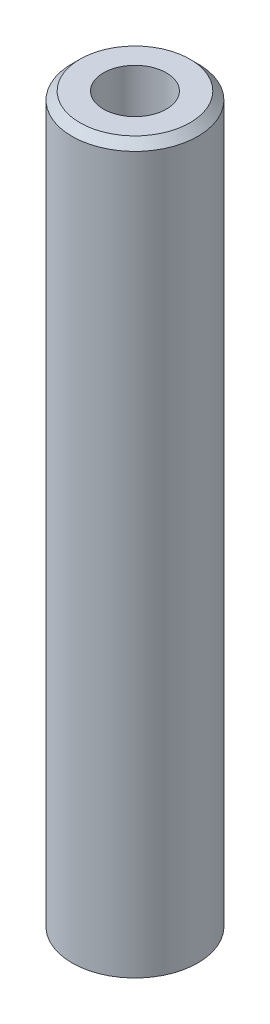
SolidWorks part; units mm, degrees
ref_plane "Front Plane" through (0, 0, 0) normal (0, 0, 1) x (1, 0, 0)
ref_plane "Top Plane" through (0, 0, 0) normal (0, 1, 0) x (1, 0, 0)
ref_plane "Right Plane" through (0, 0, 0) normal (1, 0, 0) x (0, 0, -1)
sketch "Sketch1" plane through (0, 0, 0) normal (0, 1, 0) x (1, 0, 0)
  circle A0 centre (0, 0) radius 2
  circle A1 centre (0, 0) radius 4
  dimension "D1" = 4
  dimension "D2" = 2
extrude "Boss-Extrude1" add sketch "Sketch1" along normal blind 46
chamfer "Chamfer1" distance 0.5 angle 45 1 edges at (0, 46, 4)
